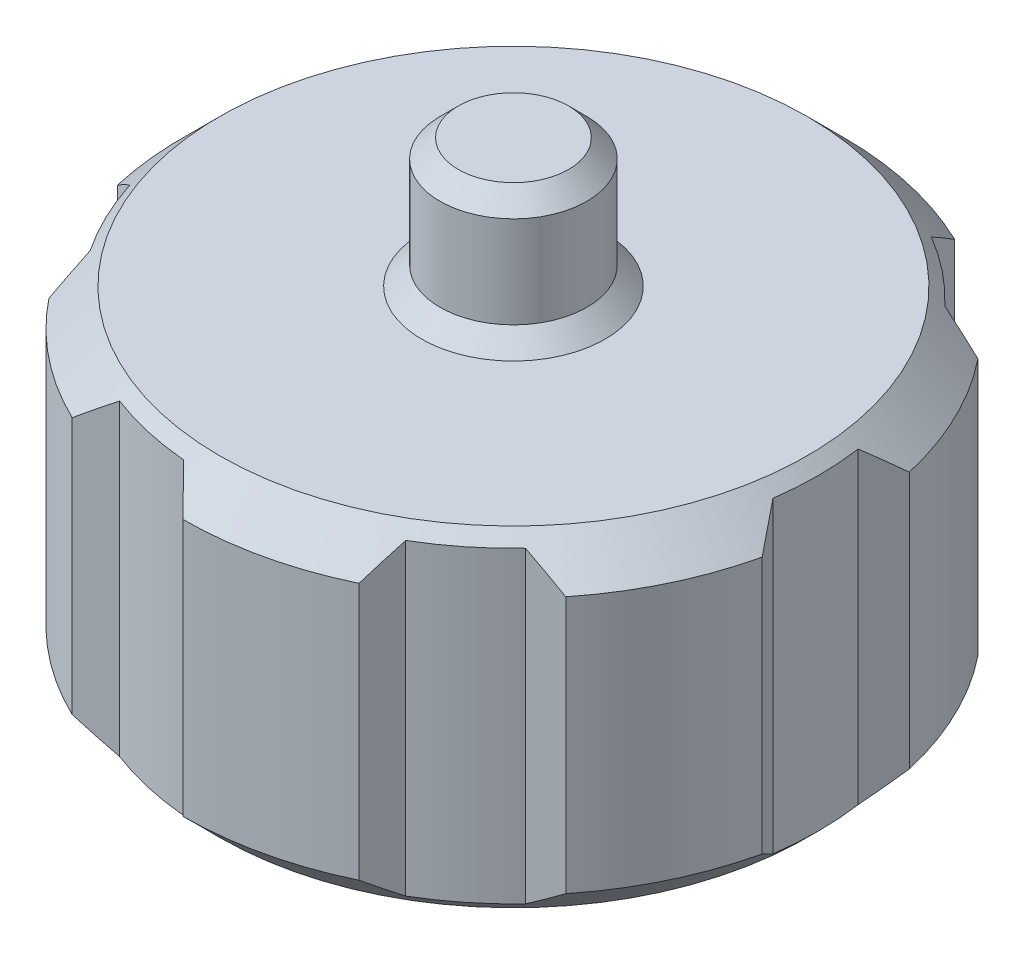
SolidWorks part; units mm, degrees
ref_plane "Alzado" through (0, 0, 0) normal (0, 0, 1) x (1, 0, 0)
ref_plane "Planta" through (0, 0, 0) normal (0, 1, 0) x (1, 0, 0)
ref_plane "Vista lateral" through (0, 0, 0) normal (1, 0, 0) x (0, 0, -1)
sketch "Croquis1" plane through (0, 0, 0) normal (0, 0, 1) x (1, 0, 0)
  line L0 (0, -8) -> (0, 8)
  line L1 (0, 8) -> (-1.5, 8)
  line L2 (-2, 7.5) -> (-2, 5)
  line L3 (-2.5, 4.5) -> (-8, 4.5)
  line L4 (-9, 3.5) -> (-9, -3.5)
  line L5 (-8, -4.5) -> (-2.5, -4.5)
  line L6 (-2, -5) -> (-2, -7.5)
  line L7 (-1.5, -8) -> (0, -8)
  line L8 (-1.5, 8) -> (-2, 7.5)
  line L9 (-2, -7.5) -> (-1.5, -8)
  line L10 (-2, 5) -> (-2.5, 4.5)
  line L11 (-2.5, -4.5) -> (-2, -5)
  line L12 (-8, 4.5) -> (-9, 3.5)
  line L13 (-9, -3.5) -> (-8, -4.5)
  point P3 (-2, -8)
  point P4 (-2, 8)
  point P5 (-2, 4.5)
  point P6 (-9, 4.5)
  point P7 (-9, -4.5)
  point P8 (-2, -4.5)
  dimension "D1" = 16
  dimension "D2" = 2
  dimension "D3" = 0.5
  dimension "D4" = 45
  dimension "D5" = 0.5
  dimension "D6" = 45
  dimension "D7" = 0.5
  dimension "D8" = 45
  dimension "D9" = 0.5
  dimension "D10" = 45
  dimension "D11" = 1
  dimension "D12" = 45
  dimension "D13" = 1
  dimension "D14" = 45
  dimension "D15" = 9
  dimension "D16" = 9
revolve "Revolución1" add sketch "Croquis1" angle 360 about L0
sketch "Croquis2" plane through (0, 4.5, 0) normal (0, 1, 0) x (1, 0, 0)
  line L0 (0, 0) -> (0, 9) construction
  line L1 (0, 0) -> (3.905, 8.1087) construction
  line L2 (0, 0) -> (7.0365, 5.6114) construction
  line L3 (0, 0) -> (8.7744, 2.0027) construction
  line L4 (0, 0) -> (8.7744, -2.0027) construction
  line L5 (0, 0) -> (7.0365, -5.6114) construction
  line L6 (0, 0) -> (3.905, -8.1087) construction
  line L7 (0, 0) -> (0, -9) construction
  line L8 (0, 0) -> (-3.905, -8.1087) construction
  line L9 (0, 0) -> (-7.0365, -5.6114) construction
  line L10 (0, 0) -> (-8.7744, -2.0027) construction
  line L11 (0, 0) -> (-8.7744, 2.0027) construction
  line L12 (0, 0) -> (-7.0365, 5.6114) construction
  line L13 (0, 0) -> (-3.905, 8.1087) construction
  line L14 (0, 9) -> (-0.7, 8.2783)
  line L15 (3.905, 8.1087) -> (4.222, 7.1551)
  line L16 (7.0365, 5.6114) -> (6.0358, 5.7087)
  line L17 (8.7744, 2.0027) -> (8.2264, 1.1603)
  line L18 (8.7744, -2.0027) -> (8.2265, -1.1596)
  line L19 (7.0365, -5.6114) -> (6.0362, -5.7083)
  line L20 (3.905, -8.1087) -> (4.2225, -7.1548)
  line L21 (0, -9) -> (-0.6994, -8.2783)
  line L22 (-3.905, -8.1087) -> (-2.9611, -7.7622)
  line L23 (-7.0365, -5.6114) -> (-6.9083, -4.6147)
  line L24 (-8.7744, -2.0027) -> (-7.915, -2.5245)
  line L25 (-8.7744, 2.0027) -> (-7.9152, 2.524)
  line L26 (-7.0365, 5.6114) -> (-6.9087, 4.6142)
  line L27 (-3.905, 8.1087) -> (-2.9617, 7.762)
  arc A0 (-0.7, 8.2783) -> (-2.9617, 7.762) centre (0, 0) ccw
  circle A1 centre (0, 0) radius 9 construction
  arc A2 (-6.9087, 4.6142) -> (-7.9152, 2.524) centre (0, 0) ccw
  arc A4 (-7.0365, 5.6114) -> (-8.7744, 2.0027) centre (0, 0) ccw
  arc A5 (0, 9) -> (-3.905, 8.1087) centre (0, 0) ccw
  arc A6 (6.0358, 5.7087) -> (4.222, 7.1551) centre (0, 0) ccw
  arc A7 (7.0365, 5.6114) -> (3.905, 8.1087) centre (0, 0) ccw
  arc A8 (8.2265, -1.1596) -> (8.2264, 1.1603) centre (0, 0) ccw
  arc A9 (8.7744, -2.0027) -> (8.7744, 2.0027) centre (0, 0) ccw
  arc A10 (4.2225, -7.1548) -> (6.0362, -5.7083) centre (0, 0) ccw
  arc A11 (3.905, -8.1087) -> (7.0365, -5.6114) centre (0, 0) ccw
  arc A12 (-3.905, -8.1087) -> (0, -9) centre (0, 0) ccw
  arc A13 (-2.9611, -7.7622) -> (-0.6994, -8.2783) centre (0, 0) ccw
  arc A14 (-7.915, -2.5245) -> (-6.9083, -4.6147) centre (0, 0) ccw
  arc A15 (-8.7744, -2.0027) -> (-7.0365, -5.6114) centre (0, 0) ccw
  point P21 (0, 0)
  point P50 (0, 0)
  dimension "D2" = 0.6994
  dimension "D4" = 8.3078
  dimension "D1" = 14
  dimension "D3" = 0.7
  dimension "D5" = 7
extrude "Cortar-Extruir1" cut sketch "Croquis2" against normal through all and the other way through all
